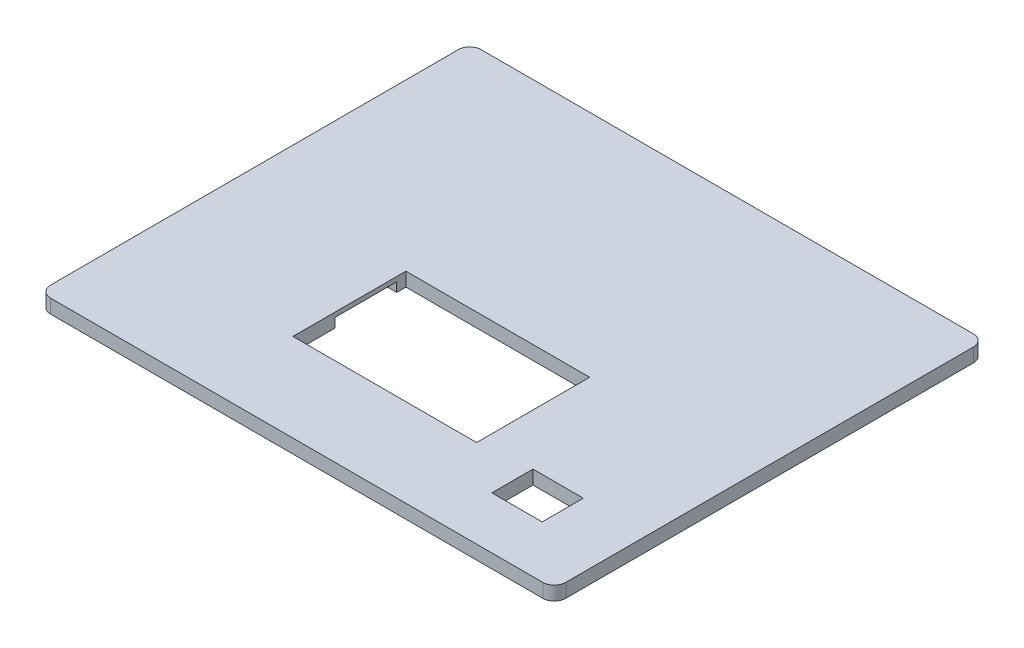
SolidWorks part; units mm, degrees
material "松木"
ref_plane "前视基准面" through (0, 0, 0) normal (0, 0, 1) x (1, 0, 0)
ref_plane "上视基准面" through (0, 0, 0) normal (0, 1, 0) x (1, 0, 0)
ref_plane "右视基准面" through (0, 0, 0) normal (1, 0, 0) x (0, 0, -1)
other "Configuration Table"
sketch "草图1" plane through (0, 0, 0) normal (0, 1, 0) x (1, 0, 0)
  line L1 (-335, 560) -> (335, 560)
  line L2 (-335, 560) -> (-335, 0)
  line L3 (-335, 0) -> (335, 0)
  line L4 (335, 560) -> (335, 0)
  point P4 (0, 0)
  dimension "D1" = 560
  dimension "D2" = 670
extrude "凸台-拉伸1" add sketch "草图1" along normal blind 18
sketch "草图2" plane through (0, 18, 0) normal (0, 1, 0) x (1, 0, 0)
  line L1 (186.0724, 121.1869) -> (251.5724, 121.1869)
  line L2 (186.0724, 121.1869) -> (186.0724, 67.6869)
  line L3 (186.0724, 67.6869) -> (251.5724, 67.6869)
  line L4 (251.5724, 121.1869) -> (251.5724, 67.6869)
  dimension "D1" = 65.5
  dimension "D2" = 53.5
extrude "切除-拉伸1" cut sketch "草图2" against normal through all both and the other way through all
sketch "草图3" plane through (0, 18, 0) normal (0, 1, 0) x (1, 0, 0)
  line L1 (-114, 256) -> (114, 256)
  line L2 (-114, 256) -> (-114, 120)
  line L3 (-114, 120) -> (114, 120)
  line L4 (114, 256) -> (114, 120)
  point P4 (0, 120)
  dimension "D1" = 136
  dimension "D2" = 228
  dimension "D3" = 120
extrude "切除-拉伸2" cut sketch "草图3" against normal through all both and the other way through all
sketch "草图4" plane through (0, 18, 0) normal (0, 1, 0) x (1, 0, 0)
  line L0 (114, 120) -> (114, 256) construction
  line L1 (-119.5, 261.5) -> (119.5, 261.5)
  line L2 (-119.5, 261.5) -> (-119.5, 114.5)
  line L3 (-119.5, 114.5) -> (119.5, 114.5)
  line L4 (119.5, 261.5) -> (119.5, 114.5)
  line L5 (114, 256) -> (-114, 256) construction
  line L6 (-114, 256) -> (-114, 120) construction
  line L7 (-114, 120) -> (114, 120) construction
  dimension "D1" = 5.5
  dimension "D2" = 5.5
  dimension "D3" = 5.5
  dimension "D4" = 5.5
extrude "切除-拉伸3" cut sketch "草图4" against normal up to next
sketch "草图7" [suppressed] plane through (0, 8, 0) normal (0, 1, 0) x (1, 0, 0)
  line L0 (-119, 115) -> (119, 115) construction
  line L1 (-119, 261) -> (-119, 115) construction
  line L2 (119, 261) -> (-119, 261) construction
  line L3 (119, 115) -> (119, 261) construction
  line L4 (-119, 115) -> (119, 115)
  line L5 (-119, 261) -> (-119, 115)
  line L6 (119, 261) -> (-119, 261)
  line L7 (119, 115) -> (119, 261)
extrude "凸台-拉伸2" [suppressed] add sketch "草图7" along normal blind 5 separate body
fillet "圆角1" radius 15 4 edges at (335, 9, -560) (335, 9, 0) (-335, 9, 0) (-335, 9, -560)
sketch "草图8" plane through (0, 0, 0) normal (0, -1, 0) x (1, 0, 0)
  line L0 (-119.5, -114.5) -> (-119.5, -261.5) construction
  line L1 (-119.5, -249.5414) -> (-199.9727, -249.5414)
  line L2 (-119.5, -249.5414) -> (-119.5, -169.5414)
  line L3 (-119.5, -169.5414) -> (-199.9727, -169.5414)
  line L4 (-199.9727, -249.5414) -> (-199.9727, -169.5414)
  dimension "D1" = 80
extrude "切除-拉伸4" cut sketch "草图8" against normal blind 12
